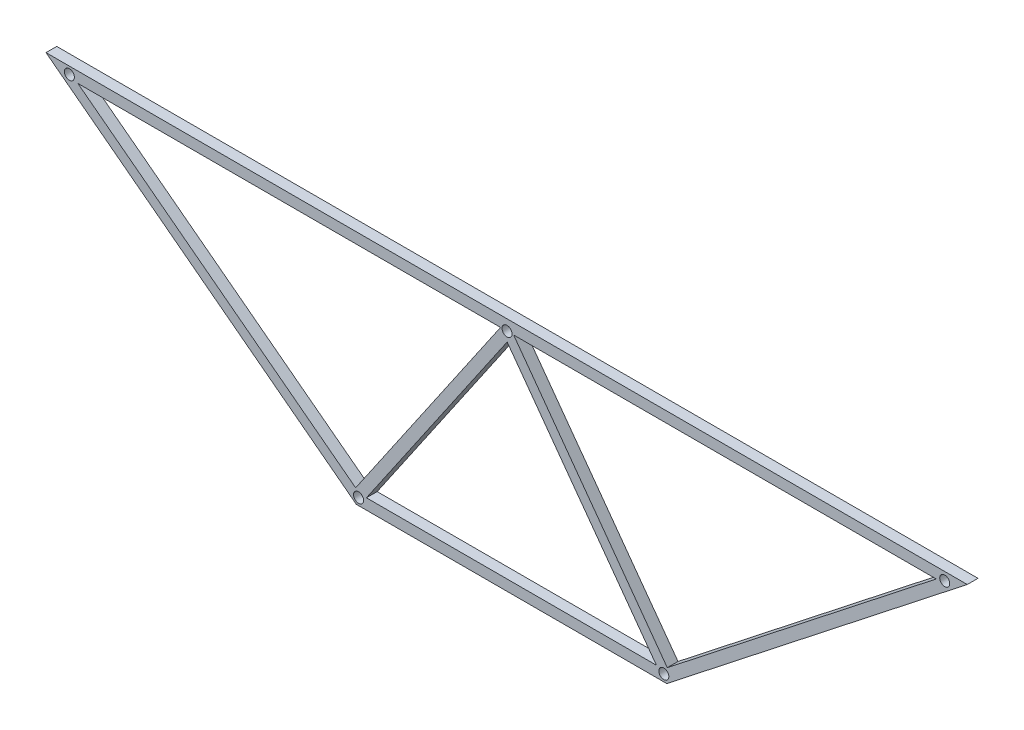
SolidWorks part; units mm, degrees
material "AISI 1035 Steel (SS)"
ref_plane "Front Plane" through (0, 0, 0) normal (0, 0, 1) x (1, 0, 0)
ref_plane "Top Plane" through (0, 0, 0) normal (0, 1, 0) x (1, 0, 0)
ref_plane "Right Plane" through (0, 0, 0) normal (1, 0, 0) x (0, 0, -1)
sketch "Sketch1" plane through (0, 0, 0) normal (0, 0, 1) x (1, 0, 0)
  line L0 (9.2729, 0) -> (600, 0)
  line L1 (-9.093, 0) -> (-600, 0)
  line L4 (208.8502, -300) -> (-196.5556, -300)
  line L6 (-600, 0) -> (-211.6249, -295.4535)
  line L7 (600, 0) -> (224.0249, -295.3636)
  line L8 (-644.4922, 15) -> (643.375, 15)
  line L9 (0, 0) -> (600, 0) construction
  line L10 (-644.4922, 15) -> (-210.7056, -315)
  line L11 (223.3104, -315) -> (-210.7056, -315)
  line L13 (643.375, 15) -> (223.3104, -315)
  line L14 (9.2729, 0) -> (224.0249, -295.3636)
  line L15 (0, 0) -> (-600, 0) construction
  line L16 (-9.093, 0) -> (-211.6249, -295.4535)
  line L17 (0.1804, -13.0017) -> (-196.5556, -300)
  line L18 (-644.4922, 15) -> (-214.7304, -311.9382) construction
  line L19 (218.1231, -315) -> (-205.6485, -315) construction
  line L20 (643.375, 15) -> (227.3895, -311.7955) construction
  line L21 (-600, 0) -> (-205.6485, -300) construction
  line L22 (218.1231, -300) -> (-205.6485, -300) construction
  line L23 (600, 0) -> (218.1231, -300) construction
  line L26 (0.1804, -13.0017) -> (208.8502, -300)
  line L28 (0, 15) -> (-644.4922, 15) construction
  line L29 (0, 15) -> (643.375, 15) construction
  dimension "D1" = 15
  dimension "D2" = 15
  dimension "D3" = 15
extrude "Boss-Extrude1" add sketch "Sketch1" along normal blind 15
sketch "Sketch2" plane through (0, 0, 15) normal (0, 0, 1) x (1, 0, 0)
  circle A0 centre (-611.8311, 4.905) radius 7
  circle A1 centre (0, 0) radius 7
  circle A2 centre (611.8791, 3.7063) radius 7
  circle A3 centre (-207.5445, -305.2116) radius 7
  circle A4 centre (219.2018, -305.2116) radius 7
  point P4 (219.0383, -305.2116)
  point P12 (218.1477, -305.2116)
  point P13 (219.2018, -305.2116)
  point P14 (0, 0)
  point P15 (0, 0)
extrude "Cut-Extrude2" cut sketch "Sketch2" against normal blind 15
